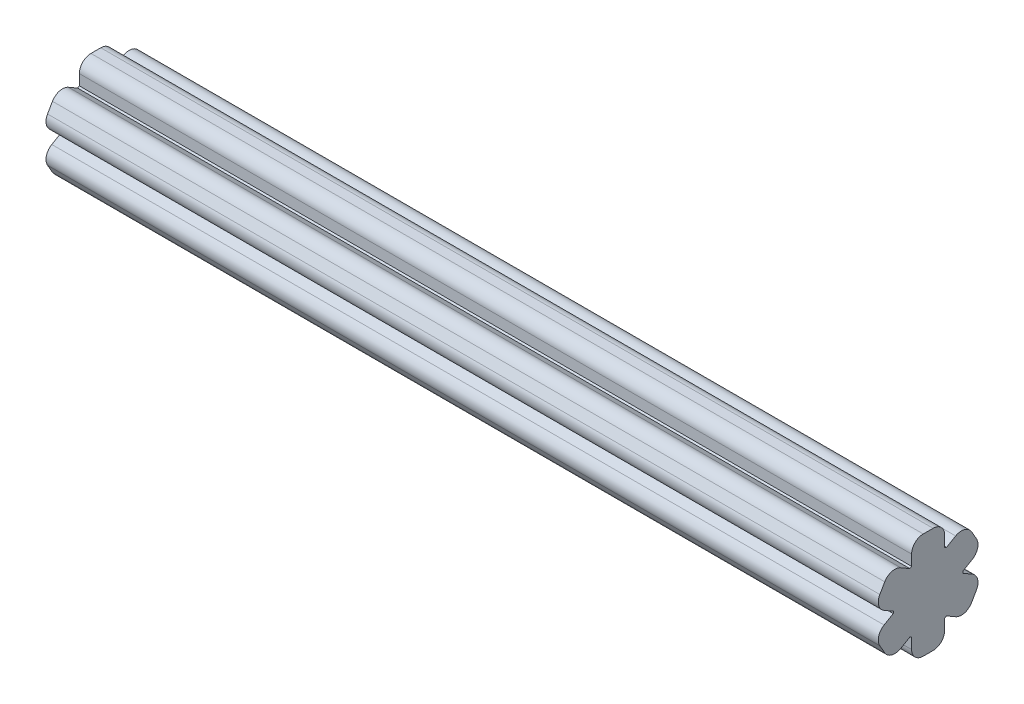
SolidWorks part; units mm, degrees
other "Markup1"
sketch "Sketch9" plane through (0, -25.79, -25.79) normal (-1, 0, 0) x (0, 1, 0)
ref_plane "Front Plane" through (0, 0, 0) normal (0, 0, 1) x (1, 0, 0)
ref_plane "Top Plane" through (0, 0, 0) normal (0, 1, 0) x (1, 0, 0)
ref_plane "Right Plane" through (0, 0, 0) normal (1, 0, 0) x (0, 0, -1)
sketch "Sketch2" plane through (0, 0, 0) normal (1, 0, 0) x (0, 0, -1)
  line L0 (9.5217, 3.0557) -> (16.4499, 7.0557)
  line L1 (-2.1146, 17.7739) -> (-2.1146, 9.7739)
  line L2 (-2.1146, 9.7739) -> (-2.1146, 17.7739)
  line L3 (2.1146, 17.7739) -> (-2.1146, 17.7739)
  line L4 (2.1146, 9.7739) -> (2.1146, 17.7739)
  line L5 (0, 17.7739) -> (0, 0) construction
  line L6 (16.4499, 7.0557) -> (14.3353, 10.7182)
  line L7 (14.3353, 10.7182) -> (7.4071, 6.7182)
  line L8 (7.4071, -6.7182) -> (14.3353, -10.7182)
  line L9 (14.3353, -10.7182) -> (16.4499, -7.0557)
  line L10 (16.4499, -7.0557) -> (9.5217, -3.0557)
  line L11 (-2.1146, -9.7739) -> (-2.1146, -17.7739)
  line L12 (-2.1146, -17.7739) -> (2.1146, -17.7739)
  line L13 (2.1146, -17.7739) -> (2.1146, -9.7739)
  line L14 (-9.5217, -3.0557) -> (-16.4499, -7.0557)
  line L15 (-16.4499, -7.0557) -> (-14.3353, -10.7182)
  line L16 (-14.3353, -10.7182) -> (-7.4071, -6.7182)
  line L17 (-7.4071, 6.7182) -> (-14.3353, 10.7182)
  line L18 (-14.3353, 10.7182) -> (-16.4499, 7.0557)
  line L19 (-16.4499, 7.0557) -> (-9.5217, 3.0557)
  circle A0 centre (0, 0) radius 25.79
  arc A1 (-2.1146, 9.7739) -> (-7.4071, 6.7182) centre (0, 0) ccw
  arc A2 (-9.5217, 3.0557) -> (-9.5217, -3.0557) centre (0, 0) ccw
  arc A3 (-7.4071, -6.7182) -> (-2.1146, -9.7739) centre (0, 0) ccw
  arc A4 (2.1146, -9.7739) -> (7.4071, -6.7182) centre (0, 0) ccw
  arc A5 (9.5217, -3.0557) -> (9.5217, 3.0557) centre (0, 0) ccw
  arc A6 (7.4071, 6.7182) -> (2.1146, 9.7739) centre (0, 0) ccw
  point P32 (0, 0)
  dimension "D1" = 6
  dimension "D2" = 51.58
  dimension "D4" = 4.2291
  dimension "10" = 10
  dimension "D3" = 8
extrude "Boss-Extrude2" add sketch "Sketch2" along normal blind 358 contours A0 | L17 L18 L19 A2 L14 L15 L16 A3 L11 L12 L13 A4 L8 L9 L10 A5 L0 L6 L7 A6 L4 L3 L1 A1
sketch "Sketch3" plane through (0, 0, 0) normal (-1, 0, 0) x (0, 0, 1)
  line L262 (-3.1146, -10.5499) -> (-3.1146, -18.7739)
  line L263 (-3.1146, -18.7739) -> (3.1146, -18.7739)
  line L264 (3.1146, -18.7739) -> (3.1146, -10.5499)
  line L265 (7.5792, -7.9722) -> (14.7014, -12.0842)
  line L266 (14.7014, -12.0842) -> (17.8159, -6.6896)
  line L267 (17.8159, -6.6896) -> (10.6937, -2.5776)
  line L268 (10.6937, 2.5776) -> (17.8159, 6.6896)
  line L269 (17.8159, 6.6896) -> (14.7014, 12.0842)
  line L270 (14.7014, 12.0842) -> (7.5792, 7.9722)
  line L271 (3.1146, 10.5499) -> (3.1146, 18.7739)
  line L272 (3.1146, 18.7739) -> (-3.1146, 18.7739)
  line L273 (-3.1146, 18.7739) -> (-3.1146, 10.5499)
  line L274 (-7.5792, 7.9722) -> (-14.7014, 12.0842)
  line L275 (-14.7014, 12.0842) -> (-17.8159, 6.6896)
  line L276 (-17.8159, 6.6896) -> (-10.6937, 2.5776)
  line L277 (-10.6937, -2.5776) -> (-17.8159, -6.6896)
  line L278 (-14.7014, -12.0842) -> (-7.5792, -7.9722)
  line L279 (-17.8159, -6.6896) -> (-14.7014, -12.0842)
  line L280 (-3.1146, -10.5499) -> (-3.1146, -17.7739)
  line L281 (-2.1146, -18.7739) -> (2.1146, -18.7739)
  line L282 (3.1146, -17.7739) -> (3.1146, -10.5499)
  line L283 (7.5792, -7.9722) -> (13.8353, -11.5842)
  line L284 (15.2014, -11.2182) -> (17.3159, -7.5557)
  line L285 (16.9499, -6.1896) -> (10.6937, -2.5776)
  line L286 (10.6937, 2.5776) -> (16.9499, 6.1896)
  line L287 (17.3159, 7.5557) -> (15.2014, 11.2182)
  line L288 (13.8353, 11.5842) -> (7.5792, 7.9722)
  line L289 (3.1146, 10.5499) -> (3.1146, 17.7739)
  line L290 (2.1146, 18.7739) -> (-2.1146, 18.7739)
  line L291 (-3.1146, 17.7739) -> (-3.1146, 10.5499)
  line L292 (-7.5792, 7.9722) -> (-13.8353, 11.5842)
  line L293 (-15.2014, 11.2182) -> (-17.3159, 7.5557)
  line L294 (-16.9499, 6.1896) -> (-10.6937, 2.5776)
  line L295 (-10.6937, -2.5776) -> (-16.9499, -6.1896)
  line L296 (-13.8353, -11.5842) -> (-7.5792, -7.9722)
  line L297 (-17.3159, -7.5557) -> (-15.2014, -11.2182)
  arc A69 (-3.1146, -17.7739) -> (-2.1146, -18.7739) centre (-2.1146, -17.7739) ccw
  arc A70 (2.1146, -18.7739) -> (3.1146, -17.7739) centre (2.1146, -17.7739) ccw
  arc A71 (13.8353, -11.5842) -> (15.2014, -11.2182) centre (14.3353, -10.7182) ccw
  arc A72 (17.3159, -7.5557) -> (16.9499, -6.1896) centre (16.4499, -7.0557) ccw
  arc A73 (16.9499, 6.1896) -> (17.3159, 7.5557) centre (16.4499, 7.0557) ccw
  arc A74 (15.2014, 11.2182) -> (13.8353, 11.5842) centre (14.3353, 10.7182) ccw
  arc A75 (-7.5792, -7.9722) -> (-3.1146, -10.5499) centre (0, 0) ccw
  arc A76 (3.1146, -10.5499) -> (7.5792, -7.9722) centre (0, 0) ccw
  arc A77 (10.6937, -2.5776) -> (10.6937, 2.5776) centre (0, 0) ccw
  arc A78 (7.5792, 7.9722) -> (3.1146, 10.5499) centre (0, 0) ccw
  arc A79 (-3.1146, 10.5499) -> (-7.5792, 7.9722) centre (0, 0) ccw
  arc A80 (-10.6937, 2.5776) -> (-10.6937, -2.5776) centre (0, 0) ccw
  arc A81 (-7.5792, -7.9722) -> (-3.1146, -10.5499) centre (0, 0) ccw
  arc A82 (3.1146, -10.5499) -> (7.5792, -7.9722) centre (0, 0) ccw
  arc A83 (10.6937, -2.5776) -> (10.6937, 2.5776) centre (0, 0) ccw
  arc A84 (7.5792, 7.9722) -> (3.1146, 10.5499) centre (0, 0) ccw
  arc A85 (-3.1146, 10.5499) -> (-7.5792, 7.9722) centre (0, 0) ccw
  arc A86 (-10.6937, 2.5776) -> (-10.6937, -2.5776) centre (0, 0) ccw
  arc A87 (3.1146, 17.7739) -> (2.1146, 18.7739) centre (2.1146, 17.7739) ccw
  arc A88 (-2.1146, 18.7739) -> (-3.1146, 17.7739) centre (-2.1146, 17.7739) ccw
  arc A89 (-15.2014, 11.2182) -> (-13.8353, 11.5842) centre (-14.3353, 10.7182) cw
  arc A90 (-17.3159, 7.5557) -> (-16.9499, 6.1896) centre (-16.4499, 7.0557) ccw
  arc A91 (-16.9499, -6.1896) -> (-17.3159, -7.5557) centre (-16.4499, -7.0557) ccw
  arc A92 (-15.2014, -11.2182) -> (-13.8353, -11.5842) centre (-14.3353, -10.7182) ccw
  point P41 (-9.7909, -2.6337)
  point P43 (0, 0)
  point P46 (-9.7344, -2.2892)
  point P47 (0, 0)
  dimension "D2" = 1
  dimension "D1" = 1
sketch "Sketch5" plane through (0, 0, 0) normal (-1, 0, 0) x (0, 0, 1)
  line L72 (-4.1146, -11.2725) -> (-4.1146, -17.7739)
  line L73 (-2.1146, -19.7739) -> (2.1146, -19.7739)
  line L74 (4.1146, -17.7739) -> (4.1146, -11.2725)
  line L75 (7.705, -9.1996) -> (13.3353, -12.4503)
  line L76 (16.0674, -11.7182) -> (18.182, -8.0557)
  line L77 (17.4499, -5.3236) -> (11.8196, -2.073)
  line L78 (11.8196, 2.073) -> (17.4499, 5.3236)
  line L79 (18.182, 8.0557) -> (16.0674, 11.7182)
  line L80 (13.3353, 12.4503) -> (7.705, 9.1996)
  line L81 (4.1146, 11.2725) -> (4.1146, 17.7739)
  line L82 (2.1146, 19.7739) -> (-2.1146, 19.7739)
  line L83 (-4.1146, 17.7739) -> (-4.1146, 11.2725)
  line L84 (-7.705, 9.1996) -> (-13.3353, 12.4503)
  line L85 (-16.0674, 11.7182) -> (-18.182, 8.0557)
  line L86 (-17.4499, 5.3236) -> (-11.8196, 2.073)
  line L87 (-11.8196, -2.073) -> (-17.4499, -5.3236)
  line L88 (-18.182, -8.0557) -> (-16.0674, -11.7182)
  line L89 (-13.3353, -12.4503) -> (-7.705, -9.1996)
  line L90 (-4.1146, -11.2725) -> (-4.1146, -17.7739)
  line L91 (-2.1146, -19.7739) -> (2.1146, -19.7739)
  line L92 (4.1146, -17.7739) -> (4.1146, -11.2725)
  line L93 (7.705, -9.1996) -> (13.3353, -12.4503)
  line L94 (16.0674, -11.7182) -> (18.182, -8.0557)
  line L95 (17.4499, -5.3236) -> (11.8196, -2.073)
  line L96 (11.8196, 2.073) -> (17.4499, 5.3236)
  line L97 (18.182, 8.0557) -> (16.0674, 11.7182)
  line L98 (13.3353, 12.4503) -> (7.705, 9.1996)
  line L99 (4.1146, 11.2725) -> (4.1146, 17.7739)
  line L100 (2.1146, 19.7739) -> (-2.1146, 19.7739)
  line L101 (-4.1146, 17.7739) -> (-4.1146, 11.2725)
  line L102 (-7.705, 9.1996) -> (-13.3353, 12.4503)
  line L103 (-16.0674, 11.7182) -> (-18.182, 8.0557)
  line L104 (-17.4499, 5.3236) -> (-11.8196, 2.073)
  line L105 (-11.8196, -2.073) -> (-17.4499, -5.3236)
  line L106 (-18.182, -8.0557) -> (-16.0674, -11.7182)
  line L107 (-13.3353, -12.4503) -> (-7.705, -9.1996)
  arc A72 (-4.1146, -17.7739) -> (-2.1146, -19.7739) centre (-2.1146, -17.7739) ccw
  arc A73 (2.1146, -19.7739) -> (4.1146, -17.7739) centre (2.1146, -17.7739) ccw
  arc A74 (4.1146, -11.2725) -> (7.705, -9.1996) centre (0, 0) ccw
  arc A75 (13.3353, -12.4503) -> (16.0674, -11.7182) centre (14.3353, -10.7182) ccw
  arc A76 (18.182, -8.0557) -> (17.4499, -5.3236) centre (16.4499, -7.0557) ccw
  arc A77 (11.8196, -2.073) -> (11.8196, 2.073) centre (0, 0) ccw
  arc A78 (17.4499, 5.3236) -> (18.182, 8.0557) centre (16.4499, 7.0557) ccw
  arc A79 (16.0674, 11.7182) -> (13.3353, 12.4503) centre (14.3353, 10.7182) ccw
  arc A80 (7.705, 9.1996) -> (4.1146, 11.2725) centre (0, 0) ccw
  arc A81 (4.1146, 17.7739) -> (2.1146, 19.7739) centre (2.1146, 17.7739) ccw
  arc A82 (-2.1146, 19.7739) -> (-4.1146, 17.7739) centre (-2.1146, 17.7739) ccw
  arc A83 (-4.1146, 11.2725) -> (-7.705, 9.1996) centre (0, 0) ccw
  arc A84 (-13.3353, 12.4503) -> (-16.0674, 11.7182) centre (-14.3353, 10.7182) ccw
  arc A85 (-18.182, 8.0557) -> (-17.4499, 5.3236) centre (-16.4499, 7.0557) ccw
  arc A86 (-11.8196, 2.073) -> (-11.8196, -2.073) centre (0, 0) ccw
  arc A87 (-17.4499, -5.3236) -> (-18.182, -8.0557) centre (-16.4499, -7.0557) ccw
  arc A88 (-16.0674, -11.7182) -> (-13.3353, -12.4503) centre (-14.3353, -10.7182) ccw
  arc A89 (-7.705, -9.1996) -> (-4.1146, -11.2725) centre (0, 0) ccw
  arc A90 (-4.1146, -17.7739) -> (-2.1146, -19.7739) centre (-2.1146, -17.7739) ccw
  arc A91 (2.1146, -19.7739) -> (4.1146, -17.7739) centre (2.1146, -17.7739) ccw
  arc A92 (4.1146, -11.2725) -> (7.705, -9.1996) centre (0, 0) ccw
  arc A93 (13.3353, -12.4503) -> (16.0674, -11.7182) centre (14.3353, -10.7182) ccw
  arc A94 (18.182, -8.0557) -> (17.4499, -5.3236) centre (16.4499, -7.0557) ccw
  arc A95 (11.8196, -2.073) -> (11.8196, 2.073) centre (0, 0) ccw
  arc A96 (17.4499, 5.3236) -> (18.182, 8.0557) centre (16.4499, 7.0557) ccw
  arc A97 (16.0674, 11.7182) -> (13.3353, 12.4503) centre (14.3353, 10.7182) ccw
  arc A98 (7.705, 9.1996) -> (4.1146, 11.2725) centre (0, 0) ccw
  arc A99 (4.1146, 17.7739) -> (2.1146, 19.7739) centre (2.1146, 17.7739) ccw
  arc A100 (-2.1146, 19.7739) -> (-4.1146, 17.7739) centre (-2.1146, 17.7739) ccw
  arc A101 (-4.1146, 11.2725) -> (-7.705, 9.1996) centre (0, 0) ccw
  arc A102 (-13.3353, 12.4503) -> (-16.0674, 11.7182) centre (-14.3353, 10.7182) ccw
  arc A103 (-18.182, 8.0557) -> (-17.4499, 5.3236) centre (-16.4499, 7.0557) ccw
  arc A104 (-11.8196, 2.073) -> (-11.8196, -2.073) centre (0, 0) ccw
  arc A105 (-17.4499, -5.3236) -> (-18.182, -8.0557) centre (-16.4499, -7.0557) ccw
  arc A106 (-16.0674, -11.7182) -> (-13.3353, -12.4503) centre (-14.3353, -10.7182) ccw
  arc A107 (-7.705, -9.1996) -> (-4.1146, -11.2725) centre (0, 0) ccw
  dimension "D1" = 1
sketch "Sketch6" plane through (0, 0, 0) normal (-1, 0, 0) x (0, 0, 1)
  line L37 (-5.1146, -11.9516) -> (-5.1146, -17.7739)
  line L38 (-2.1146, -20.7739) -> (2.1146, -20.7739)
  line L39 (5.1146, -17.7739) -> (5.1146, -11.9516)
  line L40 (7.7931, -10.4052) -> (12.8353, -13.3163)
  line L41 (16.9334, -12.2182) -> (19.048, -8.5557)
  line L42 (17.9499, -4.4576) -> (12.9077, -1.5465)
  line L43 (12.9077, 1.5465) -> (17.9499, 4.4576)
  line L44 (19.048, 8.5557) -> (16.9334, 12.2182)
  line L45 (12.8353, 13.3163) -> (7.7931, 10.4052)
  line L46 (5.1146, 11.9516) -> (5.1146, 17.7739)
  line L47 (2.1146, 20.7739) -> (-2.1146, 20.7739)
  line L48 (-5.1146, 17.7739) -> (-5.1146, 11.9516)
  line L49 (-7.7931, 10.4052) -> (-12.8353, 13.3163)
  line L50 (-16.9334, 12.2182) -> (-19.048, 8.5557)
  line L51 (-17.9499, 4.4576) -> (-12.9077, 1.5465)
  line L52 (-12.9077, -1.5465) -> (-17.9499, -4.4576)
  line L53 (-19.048, -8.5557) -> (-16.9334, -12.2182)
  line L54 (-12.8353, -13.3163) -> (-7.7931, -10.4052)
  line L55 (-5.1146, -11.9516) -> (-5.1146, -17.7739)
  line L56 (-2.1146, -20.7739) -> (2.1146, -20.7739)
  line L57 (5.1146, -17.7739) -> (5.1146, -11.9516)
  line L58 (7.7931, -10.4052) -> (12.8353, -13.3163)
  line L59 (16.9334, -12.2182) -> (19.048, -8.5557)
  line L60 (17.9499, -4.4576) -> (12.9077, -1.5465)
  line L61 (12.9077, 1.5465) -> (17.9499, 4.4576)
  line L62 (19.048, 8.5557) -> (16.9334, 12.2182)
  line L63 (12.8353, 13.3163) -> (7.7931, 10.4052)
  line L64 (5.1146, 11.9516) -> (5.1146, 17.7739)
  line L65 (2.1146, 20.7739) -> (-2.1146, 20.7739)
  line L66 (-5.1146, 17.7739) -> (-5.1146, 11.9516)
  line L67 (-7.7931, 10.4052) -> (-12.8353, 13.3163)
  line L68 (-16.9334, 12.2182) -> (-19.048, 8.5557)
  line L69 (-17.9499, 4.4576) -> (-12.9077, 1.5465)
  line L70 (-12.9077, -1.5465) -> (-17.9499, -4.4576)
  line L71 (-19.048, -8.5557) -> (-16.9334, -12.2182)
  line L72 (-12.8353, -13.3163) -> (-7.7931, -10.4052)
  arc A36 (-5.1146, -17.7739) -> (-2.1146, -20.7739) centre (-2.1146, -17.7739) ccw
  arc A37 (2.1146, -20.7739) -> (5.1146, -17.7739) centre (2.1146, -17.7739) ccw
  arc A38 (5.1146, -11.9516) -> (7.7931, -10.4052) centre (0, 0) ccw
  arc A39 (12.8353, -13.3163) -> (16.9334, -12.2182) centre (14.3353, -10.7182) ccw
  arc A40 (19.048, -8.5557) -> (17.9499, -4.4576) centre (16.4499, -7.0557) ccw
  arc A41 (12.9077, -1.5465) -> (12.9077, 1.5465) centre (0, 0) ccw
  arc A42 (17.9499, 4.4576) -> (19.048, 8.5557) centre (16.4499, 7.0557) ccw
  arc A43 (16.9334, 12.2182) -> (12.8353, 13.3163) centre (14.3353, 10.7182) ccw
  arc A44 (7.7931, 10.4052) -> (5.1146, 11.9516) centre (0, 0) ccw
  arc A45 (5.1146, 17.7739) -> (2.1146, 20.7739) centre (2.1146, 17.7739) ccw
  arc A46 (-2.1146, 20.7739) -> (-5.1146, 17.7739) centre (-2.1146, 17.7739) ccw
  arc A47 (-5.1146, 11.9516) -> (-7.7931, 10.4052) centre (0, 0) ccw
  arc A48 (-12.8353, 13.3163) -> (-16.9334, 12.2182) centre (-14.3353, 10.7182) ccw
  arc A49 (-19.048, 8.5557) -> (-17.9499, 4.4576) centre (-16.4499, 7.0557) ccw
  arc A50 (-12.9077, 1.5465) -> (-12.9077, -1.5465) centre (0, 0) ccw
  arc A51 (-17.9499, -4.4576) -> (-19.048, -8.5557) centre (-16.4499, -7.0557) ccw
  arc A52 (-16.9334, -12.2182) -> (-12.8353, -13.3163) centre (-14.3353, -10.7182) ccw
  arc A53 (-7.7931, -10.4052) -> (-5.1146, -11.9516) centre (0, 0) ccw
  arc A54 (-5.1146, -17.7739) -> (-2.1146, -20.7739) centre (-2.1146, -17.7739) ccw
  arc A55 (2.1146, -20.7739) -> (5.1146, -17.7739) centre (2.1146, -17.7739) ccw
  arc A56 (5.1146, -11.9516) -> (7.7931, -10.4052) centre (0, 0) ccw
  arc A57 (12.8353, -13.3163) -> (16.9334, -12.2182) centre (14.3353, -10.7182) ccw
  arc A58 (19.048, -8.5557) -> (17.9499, -4.4576) centre (16.4499, -7.0557) ccw
  arc A59 (12.9077, -1.5465) -> (12.9077, 1.5465) centre (0, 0) ccw
  arc A60 (17.9499, 4.4576) -> (19.048, 8.5557) centre (16.4499, 7.0557) ccw
  arc A61 (16.9334, 12.2182) -> (12.8353, 13.3163) centre (14.3353, 10.7182) ccw
  arc A62 (7.7931, 10.4052) -> (5.1146, 11.9516) centre (0, 0) ccw
  arc A63 (5.1146, 17.7739) -> (2.1146, 20.7739) centre (2.1146, 17.7739) ccw
  arc A64 (-2.1146, 20.7739) -> (-5.1146, 17.7739) centre (-2.1146, 17.7739) ccw
  arc A65 (-5.1146, 11.9516) -> (-7.7931, 10.4052) centre (0, 0) ccw
  arc A66 (-12.8353, 13.3163) -> (-16.9334, 12.2182) centre (-14.3353, 10.7182) ccw
  arc A67 (-19.048, 8.5557) -> (-17.9499, 4.4576) centre (-16.4499, 7.0557) ccw
  arc A68 (-12.9077, 1.5465) -> (-12.9077, -1.5465) centre (0, 0) ccw
  arc A69 (-17.9499, -4.4576) -> (-19.048, -8.5557) centre (-16.4499, -7.0557) ccw
  arc A70 (-16.9334, -12.2182) -> (-12.8353, -13.3163) centre (-14.3353, -10.7182) ccw
  arc A71 (-7.7931, -10.4052) -> (-5.1146, -11.9516) centre (0, 0) ccw
  dimension "D1" = 1
sketch "Sketch7" plane through (0, 0, 0) normal (-1, 0, 0) x (0, 0, 1)
  line L36 (-6.1146, -12.5941) -> (-6.1146, -17.7739)
  line L37 (-2.1146, -21.7739) -> (2.1146, -21.7739)
  line L38 (6.1146, -17.7739) -> (6.1146, -12.5941)
  line L39 (7.8496, -11.5924) -> (12.3353, -14.1823)
  line L40 (17.7994, -12.7182) -> (19.914, -9.0557)
  line L41 (18.4499, -3.5916) -> (13.9641, -1.0017)
  line L42 (13.9641, 1.0017) -> (18.4499, 3.5916)
  line L43 (19.914, 9.0557) -> (17.7994, 12.7182)
  line L44 (12.3353, 14.1823) -> (7.8496, 11.5924)
  line L45 (6.1146, 12.5941) -> (6.1146, 17.7739)
  line L46 (2.1146, 21.7739) -> (-2.1146, 21.7739)
  line L47 (-6.1146, 17.7739) -> (-6.1146, 12.5941)
  line L48 (-7.8496, 11.5924) -> (-12.3353, 14.1823)
  line L49 (-17.7994, 12.7182) -> (-19.914, 9.0557)
  line L50 (-18.4499, 3.5916) -> (-13.9641, 1.0017)
  line L51 (-13.9641, -1.0017) -> (-18.4499, -3.5916)
  line L52 (-19.914, -9.0557) -> (-17.7994, -12.7182)
  line L53 (-12.3353, -14.1823) -> (-7.8496, -11.5924)
  line L54 (-6.1146, -12.5941) -> (-6.1146, -17.7739)
  line L55 (-2.1146, -21.7739) -> (2.1146, -21.7739)
  line L56 (6.1146, -17.7739) -> (6.1146, -12.5941)
  line L57 (7.8496, -11.5924) -> (12.3353, -14.1823)
  line L58 (17.7994, -12.7182) -> (19.914, -9.0557)
  line L59 (18.4499, -3.5916) -> (13.9641, -1.0017)
  line L60 (13.9641, 1.0017) -> (18.4499, 3.5916)
  line L61 (19.914, 9.0557) -> (17.7994, 12.7182)
  line L62 (12.3353, 14.1823) -> (7.8496, 11.5924)
  line L63 (6.1146, 12.5941) -> (6.1146, 17.7739)
  line L64 (2.1146, 21.7739) -> (-2.1146, 21.7739)
  line L65 (-6.1146, 17.7739) -> (-6.1146, 12.5941)
  line L66 (-7.8496, 11.5924) -> (-12.3353, 14.1823)
  line L67 (-17.7994, 12.7182) -> (-19.914, 9.0557)
  line L68 (-18.4499, 3.5916) -> (-13.9641, 1.0017)
  line L69 (-13.9641, -1.0017) -> (-18.4499, -3.5916)
  line L70 (-19.914, -9.0557) -> (-17.7994, -12.7182)
  line L71 (-12.3353, -14.1823) -> (-7.8496, -11.5924)
  arc A37 (-6.1146, -17.7739) -> (-2.1146, -21.7739) centre (-2.1146, -17.7739) ccw
  arc A38 (2.1146, -21.7739) -> (6.1146, -17.7739) centre (2.1146, -17.7739) ccw
  arc A39 (6.1146, -12.5941) -> (7.8496, -11.5924) centre (0, 0) ccw
  arc A40 (12.3353, -14.1823) -> (17.7994, -12.7182) centre (14.3353, -10.7182) ccw
  arc A41 (19.914, -9.0557) -> (18.4499, -3.5916) centre (16.4499, -7.0557) ccw
  arc A42 (13.9641, -1.0017) -> (13.9641, 1.0017) centre (0, 0) ccw
  arc A43 (18.4499, 3.5916) -> (19.914, 9.0557) centre (16.4499, 7.0557) ccw
  arc A44 (17.7994, 12.7182) -> (12.3353, 14.1823) centre (14.3353, 10.7182) ccw
  arc A45 (7.8496, 11.5924) -> (6.1146, 12.5941) centre (0, 0) ccw
  arc A46 (6.1146, 17.7739) -> (2.1146, 21.7739) centre (2.1146, 17.7739) ccw
  arc A47 (-2.1146, 21.7739) -> (-6.1146, 17.7739) centre (-2.1146, 17.7739) ccw
  arc A48 (-6.1146, 12.5941) -> (-7.8496, 11.5924) centre (0, 0) ccw
  arc A49 (-12.3353, 14.1823) -> (-17.7994, 12.7182) centre (-14.3353, 10.7182) ccw
  arc A50 (-19.914, 9.0557) -> (-18.4499, 3.5916) centre (-16.4499, 7.0557) ccw
  arc A51 (-13.9641, 1.0017) -> (-13.9641, -1.0017) centre (0, 0) ccw
  arc A52 (-18.4499, -3.5916) -> (-19.914, -9.0557) centre (-16.4499, -7.0557) ccw
  arc A53 (-17.7994, -12.7182) -> (-12.3353, -14.1823) centre (-14.3353, -10.7182) ccw
  arc A54 (-7.8496, -11.5924) -> (-6.1146, -12.5941) centre (0, 0) ccw
  arc A55 (-6.1146, -17.7739) -> (-2.1146, -21.7739) centre (-2.1146, -17.7739) ccw
  arc A56 (2.1146, -21.7739) -> (6.1146, -17.7739) centre (2.1146, -17.7739) ccw
  arc A57 (6.1146, -12.5941) -> (7.8496, -11.5924) centre (0, 0) ccw
  arc A58 (12.3353, -14.1823) -> (17.7994, -12.7182) centre (14.3353, -10.7182) ccw
  arc A59 (19.914, -9.0557) -> (18.4499, -3.5916) centre (16.4499, -7.0557) ccw
  arc A60 (13.9641, -1.0017) -> (13.9641, 1.0017) centre (0, 0) ccw
  arc A61 (18.4499, 3.5916) -> (19.914, 9.0557) centre (16.4499, 7.0557) ccw
  arc A62 (17.7994, 12.7182) -> (12.3353, 14.1823) centre (14.3353, 10.7182) ccw
  arc A63 (7.8496, 11.5924) -> (6.1146, 12.5941) centre (0, 0) ccw
  arc A64 (6.1146, 17.7739) -> (2.1146, 21.7739) centre (2.1146, 17.7739) ccw
  arc A65 (-2.1146, 21.7739) -> (-6.1146, 17.7739) centre (-2.1146, 17.7739) ccw
  arc A66 (-6.1146, 12.5941) -> (-7.8496, 11.5924) centre (0, 0) ccw
  arc A67 (-12.3353, 14.1823) -> (-17.7994, 12.7182) centre (-14.3353, 10.7182) ccw
  arc A68 (-19.914, 9.0557) -> (-18.4499, 3.5916) centre (-16.4499, 7.0557) ccw
  arc A69 (-13.9641, 1.0017) -> (-13.9641, -1.0017) centre (0, 0) ccw
  arc A70 (-18.4499, -3.5916) -> (-19.914, -9.0557) centre (-16.4499, -7.0557) ccw
  arc A71 (-17.7994, -12.7182) -> (-12.3353, -14.1823) centre (-14.3353, -10.7182) ccw
  arc A72 (-7.8496, -11.5924) -> (-6.1146, -12.5941) centre (0, 0) ccw
  dimension "D1" = 1
sketch "Sketch10" plane through (0, 0, 0) normal (-1, 0, 0) x (0, 0, 1)
  line L36 (-7.1146, -13.2054) -> (-7.1146, -17.7739)
  line L37 (-2.1146, -22.7739) -> (2.1146, -22.7739)
  line L38 (7.1146, -17.7739) -> (7.1146, -13.2054)
  line L39 (7.8789, -12.7641) -> (11.8353, -15.0483)
  line L40 (18.6655, -13.2182) -> (20.78, -9.5557)
  line L41 (18.9499, -2.7255) -> (14.9935, -0.4413)
  line L42 (14.9935, 0.4413) -> (18.9499, 2.7255)
  line L43 (20.78, 9.5557) -> (18.6655, 13.2182)
  line L44 (11.8353, 15.0483) -> (7.8789, 12.7641)
  line L45 (7.1146, 13.2054) -> (7.1146, 17.7739)
  line L46 (2.1146, 22.7739) -> (-2.1146, 22.7739)
  line L47 (-7.1146, 17.7739) -> (-7.1146, 13.2054)
  line L48 (-7.8789, 12.7641) -> (-11.8353, 15.0483)
  line L49 (-18.6655, 13.2182) -> (-20.78, 9.5557)
  line L50 (-18.9499, 2.7255) -> (-14.9935, 0.4413)
  line L51 (-14.9935, -0.4413) -> (-18.9499, -2.7255)
  line L52 (-20.78, -9.5557) -> (-18.6655, -13.2182)
  line L53 (-11.8353, -15.0483) -> (-7.8789, -12.7641)
  line L54 (-7.1146, -13.2054) -> (-7.1146, -17.7739)
  line L55 (-2.1146, -22.7739) -> (2.1146, -22.7739)
  line L56 (7.1146, -17.7739) -> (7.1146, -13.2054)
  line L57 (7.8789, -12.7641) -> (11.8353, -15.0483)
  line L58 (18.6655, -13.2182) -> (20.78, -9.5557)
  line L59 (18.9499, -2.7255) -> (14.9935, -0.4413)
  line L60 (14.9935, 0.4413) -> (18.9499, 2.7255)
  line L61 (20.78, 9.5557) -> (18.6655, 13.2182)
  line L62 (11.8353, 15.0483) -> (7.8789, 12.7641)
  line L63 (7.1146, 13.2054) -> (7.1146, 17.7739)
  line L64 (2.1146, 22.7739) -> (-2.1146, 22.7739)
  line L65 (-7.1146, 17.7739) -> (-7.1146, 13.2054)
  line L66 (-7.8789, 12.7641) -> (-11.8353, 15.0483)
  line L67 (-18.6655, 13.2182) -> (-20.78, 9.5557)
  line L68 (-18.9499, 2.7255) -> (-14.9935, 0.4413)
  line L69 (-14.9935, -0.4413) -> (-18.9499, -2.7255)
  line L70 (-20.78, -9.5557) -> (-18.6655, -13.2182)
  line L71 (-11.8353, -15.0483) -> (-7.8789, -12.7641)
  arc A36 (-7.1146, -17.7739) -> (-2.1146, -22.7739) centre (-2.1146, -17.7739) ccw
  arc A37 (2.1146, -22.7739) -> (7.1146, -17.7739) centre (2.1146, -17.7739) ccw
  arc A38 (7.1146, -13.2054) -> (7.8789, -12.7641) centre (0, 0) ccw
  arc A39 (11.8353, -15.0483) -> (18.6655, -13.2182) centre (14.3353, -10.7182) ccw
  arc A40 (20.78, -9.5557) -> (18.9499, -2.7255) centre (16.4499, -7.0557) ccw
  arc A41 (14.9935, -0.4413) -> (14.9935, 0.4413) centre (0, 0) ccw
  arc A42 (18.9499, 2.7255) -> (20.78, 9.5557) centre (16.4499, 7.0557) ccw
  arc A43 (18.6655, 13.2182) -> (11.8353, 15.0483) centre (14.3353, 10.7182) ccw
  arc A44 (7.8789, 12.7641) -> (7.1146, 13.2054) centre (0, 0) ccw
  arc A45 (7.1146, 17.7739) -> (2.1146, 22.7739) centre (2.1146, 17.7739) ccw
  arc A46 (-2.1146, 22.7739) -> (-7.1146, 17.7739) centre (-2.1146, 17.7739) ccw
  arc A47 (-7.1146, 13.2054) -> (-7.8789, 12.7641) centre (0, 0) ccw
  arc A48 (-11.8353, 15.0483) -> (-18.6655, 13.2182) centre (-14.3353, 10.7182) ccw
  arc A49 (-20.78, 9.5557) -> (-18.9499, 2.7255) centre (-16.4499, 7.0557) ccw
  arc A50 (-14.9935, 0.4413) -> (-14.9935, -0.4413) centre (0, 0) ccw
  arc A51 (-18.9499, -2.7255) -> (-20.78, -9.5557) centre (-16.4499, -7.0557) ccw
  arc A52 (-18.6655, -13.2182) -> (-11.8353, -15.0483) centre (-14.3353, -10.7182) ccw
  arc A53 (-7.8789, -12.7641) -> (-7.1146, -13.2054) centre (0, 0) ccw
  arc A54 (-7.1146, -17.7739) -> (-2.1146, -22.7739) centre (-2.1146, -17.7739) ccw
  arc A55 (2.1146, -22.7739) -> (7.1146, -17.7739) centre (2.1146, -17.7739) ccw
  arc A56 (7.1146, -13.2054) -> (7.8789, -12.7641) centre (0, 0) ccw
  arc A57 (11.8353, -15.0483) -> (18.6655, -13.2182) centre (14.3353, -10.7182) ccw
  arc A58 (20.78, -9.5557) -> (18.9499, -2.7255) centre (16.4499, -7.0557) ccw
  arc A59 (14.9935, -0.4413) -> (14.9935, 0.4413) centre (0, 0) ccw
  arc A60 (18.9499, 2.7255) -> (20.78, 9.5557) centre (16.4499, 7.0557) ccw
  arc A61 (18.6655, 13.2182) -> (11.8353, 15.0483) centre (14.3353, 10.7182) ccw
  arc A62 (7.8789, 12.7641) -> (7.1146, 13.2054) centre (0, 0) ccw
  arc A63 (7.1146, 17.7739) -> (2.1146, 22.7739) centre (2.1146, 17.7739) ccw
  arc A64 (-2.1146, 22.7739) -> (-7.1146, 17.7739) centre (-2.1146, 17.7739) ccw
  arc A65 (-7.1146, 13.2054) -> (-7.8789, 12.7641) centre (0, 0) ccw
  arc A66 (-11.8353, 15.0483) -> (-18.6655, 13.2182) centre (-14.3353, 10.7182) ccw
  arc A67 (-20.78, 9.5557) -> (-18.9499, 2.7255) centre (-16.4499, 7.0557) ccw
  arc A68 (-14.9935, 0.4413) -> (-14.9935, -0.4413) centre (0, 0) ccw
  arc A69 (-18.9499, -2.7255) -> (-20.78, -9.5557) centre (-16.4499, -7.0557) ccw
  arc A70 (-18.6655, -13.2182) -> (-11.8353, -15.0483) centre (-14.3353, -10.7182) ccw
  arc A71 (-7.8789, -12.7641) -> (-7.1146, -13.2054) centre (0, 0) ccw
  dimension "D1" = 1
sketch "Sketch11" plane through (0, 0, 0) normal (-1, 0, 0) x (0, 0, 1)
  line L36 (-8.1146, -14.0548) -> (-8.1146, -17.7739)
  line L37 (-2.1146, -23.7739) -> (2.1146, -23.7739)
  line L38 (8.1146, -17.7739) -> (8.1146, -14.0548)
  line L39 (8.1146, -14.0548) -> (11.3353, -15.9144)
  line L40 (19.5315, -13.7182) -> (21.6461, -10.0557)
  line L41 (19.4499, -1.8595) -> (16.2291, 0)
  line L42 (16.2291, 0) -> (19.4499, 1.8595)
  line L43 (21.6461, 10.0557) -> (19.5315, 13.7182)
  line L44 (11.3353, 15.9144) -> (8.1146, 14.0548)
  line L45 (8.1146, 14.0548) -> (8.1146, 17.7739)
  line L46 (2.1146, 23.7739) -> (-2.1146, 23.7739)
  line L47 (-8.1146, 17.7739) -> (-8.1146, 14.0548)
  line L48 (-8.1146, 14.0548) -> (-11.3353, 15.9144)
  line L49 (-19.5315, 13.7182) -> (-21.6461, 10.0557)
  line L50 (-19.4499, 1.8595) -> (-16.2291, 0)
  line L51 (-16.2291, 0) -> (-19.4499, -1.8595)
  line L52 (-21.6461, -10.0557) -> (-19.5315, -13.7182)
  line L53 (-11.3353, -15.9144) -> (-8.1146, -14.0548)
  line L54 (-8.1146, -14.0548) -> (-8.1146, -17.7739)
  line L55 (-2.1146, -23.7739) -> (2.1146, -23.7739)
  line L56 (8.1146, -17.7739) -> (8.1146, -14.0548)
  line L57 (8.1146, -14.0548) -> (11.3353, -15.9144)
  line L58 (19.5315, -13.7182) -> (21.6461, -10.0557)
  line L59 (19.4499, -1.8595) -> (16.2291, 0)
  line L60 (16.2291, 0) -> (19.4499, 1.8595)
  line L61 (21.6461, 10.0557) -> (19.5315, 13.7182)
  line L62 (11.3353, 15.9144) -> (8.1146, 14.0548)
  line L63 (8.1146, 14.0548) -> (8.1146, 17.7739)
  line L64 (2.1146, 23.7739) -> (-2.1146, 23.7739)
  line L65 (-8.1146, 17.7739) -> (-8.1146, 14.0548)
  line L66 (-8.1146, 14.0548) -> (-11.3353, 15.9144)
  line L67 (-19.5315, 13.7182) -> (-21.6461, 10.0557)
  line L68 (-19.4499, 1.8595) -> (-16.2291, 0)
  line L69 (-16.2291, 0) -> (-19.4499, -1.8595)
  line L70 (-21.6461, -10.0557) -> (-19.5315, -13.7182)
  line L71 (-11.3353, -15.9144) -> (-8.1146, -14.0548)
  arc A36 (-8.1146, -17.7739) -> (-2.1146, -23.7739) centre (-2.1146, -17.7739) ccw
  arc A37 (2.1146, -23.7739) -> (8.1146, -17.7739) centre (2.1146, -17.7739) ccw
  arc A38 (11.3353, -15.9144) -> (19.5315, -13.7182) centre (14.3353, -10.7182) ccw
  arc A39 (21.6461, -10.0557) -> (19.4499, -1.8595) centre (16.4499, -7.0557) ccw
  arc A40 (19.4499, 1.8595) -> (21.6461, 10.0557) centre (16.4499, 7.0557) ccw
  arc A41 (19.5315, 13.7182) -> (11.3353, 15.9144) centre (14.3353, 10.7182) ccw
  arc A42 (8.1146, 17.7739) -> (2.1146, 23.7739) centre (2.1146, 17.7739) ccw
  arc A43 (-2.1146, 23.7739) -> (-8.1146, 17.7739) centre (-2.1146, 17.7739) ccw
  arc A44 (-11.3353, 15.9144) -> (-19.5315, 13.7182) centre (-14.3353, 10.7182) ccw
  arc A45 (-21.6461, 10.0557) -> (-19.4499, 1.8595) centre (-16.4499, 7.0557) ccw
  arc A46 (-19.4499, -1.8595) -> (-21.6461, -10.0557) centre (-16.4499, -7.0557) ccw
  arc A47 (-19.5315, -13.7182) -> (-11.3353, -15.9144) centre (-14.3353, -10.7182) ccw
  arc A48 (-8.1146, -17.7739) -> (-2.1146, -23.7739) centre (-2.1146, -17.7739) ccw
  arc A49 (2.1146, -23.7739) -> (8.1146, -17.7739) centre (2.1146, -17.7739) ccw
  arc A50 (11.3353, -15.9144) -> (19.5315, -13.7182) centre (14.3353, -10.7182) ccw
  arc A51 (21.6461, -10.0557) -> (19.4499, -1.8595) centre (16.4499, -7.0557) ccw
  arc A52 (19.4499, 1.8595) -> (21.6461, 10.0557) centre (16.4499, 7.0557) ccw
  arc A53 (19.5315, 13.7182) -> (11.3353, 15.9144) centre (14.3353, 10.7182) ccw
  arc A54 (8.1146, 17.7739) -> (2.1146, 23.7739) centre (2.1146, 17.7739) ccw
  arc A55 (-2.1146, 23.7739) -> (-8.1146, 17.7739) centre (-2.1146, 17.7739) ccw
  arc A56 (-11.3353, 15.9144) -> (-19.5315, 13.7182) centre (-14.3353, 10.7182) ccw
  arc A57 (-21.6461, 10.0557) -> (-19.4499, 1.8595) centre (-16.4499, 7.0557) ccw
  arc A58 (-19.4499, -1.8595) -> (-21.6461, -10.0557) centre (-16.4499, -7.0557) ccw
  arc A59 (-19.5315, -13.7182) -> (-11.3353, -15.9144) centre (-14.3353, -10.7182) ccw
  point P2 (0, 0)
  point P3 (-10.4593, -2.7078)
  point P4 (-7.1398, -3.4606)
  dimension "D1" = 1
sketch "Sketch12" plane through (0, 0, 0) normal (-1, 0, 0) x (0, 0, 1)
  line L36 (-9.1146, -15.7869) -> (-9.1146, -17.7739)
  line L37 (-2.1146, -24.7739) -> (2.1146, -24.7739)
  line L38 (9.1146, -17.7739) -> (9.1146, -15.7869)
  line L39 (9.1146, -15.7869) -> (10.8353, -16.7804)
  line L40 (20.3975, -14.2182) -> (22.5121, -10.5557)
  line L41 (19.9499, -0.9935) -> (18.2291, 0)
  line L42 (18.2291, 0) -> (19.9499, 0.9935)
  line L43 (22.5121, 10.5557) -> (20.3975, 14.2182)
  line L44 (10.8353, 16.7804) -> (9.1146, 15.7869)
  line L45 (9.1146, 15.7869) -> (9.1146, 17.7739)
  line L46 (2.1146, 24.7739) -> (-2.1146, 24.7739)
  line L47 (-9.1146, 17.7739) -> (-9.1146, 15.7869)
  line L48 (-9.1146, 15.7869) -> (-10.8353, 16.7804)
  line L49 (-20.3975, 14.2182) -> (-22.5121, 10.5557)
  line L50 (-19.9499, 0.9935) -> (-18.2291, 0)
  line L51 (-18.2291, 0) -> (-19.9499, -0.9935)
  line L52 (-22.5121, -10.5557) -> (-20.3975, -14.2182)
  line L53 (-10.8353, -16.7804) -> (-9.1146, -15.7869)
  line L54 (-9.1146, -15.7869) -> (-9.1146, -17.7739)
  line L55 (-2.1146, -24.7739) -> (2.1146, -24.7739)
  line L56 (9.1146, -17.7739) -> (9.1146, -15.7869)
  line L57 (9.1146, -15.7869) -> (10.8353, -16.7804)
  line L58 (20.3975, -14.2182) -> (22.5121, -10.5557)
  line L59 (19.9499, -0.9935) -> (18.2291, 0)
  line L60 (18.2291, 0) -> (19.9499, 0.9935)
  line L61 (22.5121, 10.5557) -> (20.3975, 14.2182)
  line L62 (10.8353, 16.7804) -> (9.1146, 15.7869)
  line L63 (9.1146, 15.7869) -> (9.1146, 17.7739)
  line L64 (2.1146, 24.7739) -> (-2.1146, 24.7739)
  line L65 (-9.1146, 17.7739) -> (-9.1146, 15.7869)
  line L66 (-9.1146, 15.7869) -> (-10.8353, 16.7804)
  line L67 (-20.3975, 14.2182) -> (-22.5121, 10.5557)
  line L68 (-19.9499, 0.9935) -> (-18.2291, 0)
  line L69 (-18.2291, 0) -> (-19.9499, -0.9935)
  line L70 (-22.5121, -10.5557) -> (-20.3975, -14.2182)
  line L71 (-10.8353, -16.7804) -> (-9.1146, -15.7869)
  arc A24 (-9.1146, -17.7739) -> (-2.1146, -24.7739) centre (-2.1146, -17.7739) ccw
  arc A25 (2.1146, -24.7739) -> (9.1146, -17.7739) centre (2.1146, -17.7739) ccw
  arc A26 (10.8353, -16.7804) -> (20.3975, -14.2182) centre (14.3353, -10.7182) ccw
  arc A27 (22.5121, -10.5557) -> (19.9499, -0.9935) centre (16.4499, -7.0557) ccw
  arc A28 (19.9499, 0.9935) -> (22.5121, 10.5557) centre (16.4499, 7.0557) ccw
  arc A29 (20.3975, 14.2182) -> (10.8353, 16.7804) centre (14.3353, 10.7182) ccw
  arc A30 (9.1146, 17.7739) -> (2.1146, 24.7739) centre (2.1146, 17.7739) ccw
  arc A31 (-2.1146, 24.7739) -> (-9.1146, 17.7739) centre (-2.1146, 17.7739) ccw
  arc A32 (-10.8353, 16.7804) -> (-20.3975, 14.2182) centre (-14.3353, 10.7182) ccw
  arc A33 (-22.5121, 10.5557) -> (-19.9499, 0.9935) centre (-16.4499, 7.0557) ccw
  arc A34 (-19.9499, -0.9935) -> (-22.5121, -10.5557) centre (-16.4499, -7.0557) ccw
  arc A35 (-20.3975, -14.2182) -> (-10.8353, -16.7804) centre (-14.3353, -10.7182) ccw
  arc A36 (-9.1146, -17.7739) -> (-2.1146, -24.7739) centre (-2.1146, -17.7739) ccw
  arc A37 (2.1146, -24.7739) -> (9.1146, -17.7739) centre (2.1146, -17.7739) ccw
  arc A38 (10.8353, -16.7804) -> (20.3975, -14.2182) centre (14.3353, -10.7182) ccw
  arc A39 (22.5121, -10.5557) -> (19.9499, -0.9935) centre (16.4499, -7.0557) ccw
  arc A40 (19.9499, 0.9935) -> (22.5121, 10.5557) centre (16.4499, 7.0557) ccw
  arc A41 (20.3975, 14.2182) -> (10.8353, 16.7804) centre (14.3353, 10.7182) ccw
  arc A42 (9.1146, 17.7739) -> (2.1146, 24.7739) centre (2.1146, 17.7739) ccw
  arc A43 (-2.1146, 24.7739) -> (-9.1146, 17.7739) centre (-2.1146, 17.7739) ccw
  arc A44 (-10.8353, 16.7804) -> (-20.3975, 14.2182) centre (-14.3353, 10.7182) ccw
  arc A45 (-22.5121, 10.5557) -> (-19.9499, 0.9935) centre (-16.4499, 7.0557) ccw
  arc A46 (-19.9499, -0.9935) -> (-22.5121, -10.5557) centre (-16.4499, -7.0557) ccw
  arc A47 (-20.3975, -14.2182) -> (-10.8353, -16.7804) centre (-14.3353, -10.7182) ccw
  dimension "D1" = 1
sketch "Sketch13" plane through (0, 0, 0) normal (-1, 0, 0) x (0, 0, 1)
  line L36 (-10.1146, -17.5189) -> (-10.1146, -17.7739)
  line L37 (-2.1146, -25.7739) -> (2.1146, -25.7739)
  line L38 (10.1146, -17.7739) -> (10.1146, -17.5189)
  line L39 (10.1146, -17.5189) -> (10.3353, -17.6464)
  line L40 (21.2635, -14.7182) -> (23.3781, -11.0557)
  line L41 (20.4499, -0.1275) -> (20.2291, 0)
  line L42 (20.2291, 0) -> (20.4499, 0.1275)
  line L43 (23.3781, 11.0557) -> (21.2635, 14.7182)
  line L44 (10.3353, 17.6464) -> (10.1146, 17.5189)
  line L45 (10.1146, 17.5189) -> (10.1146, 17.7739)
  line L46 (2.1146, 25.7739) -> (-2.1146, 25.7739)
  line L47 (-10.1146, 17.7739) -> (-10.1146, 17.5189)
  line L48 (-10.1146, 17.5189) -> (-10.3353, 17.6464)
  line L49 (-21.2635, 14.7182) -> (-23.3781, 11.0557)
  line L50 (-20.4499, 0.1275) -> (-20.2291, 0)
  line L51 (-20.2291, 0) -> (-20.4499, -0.1275)
  line L52 (-23.3781, -11.0557) -> (-21.2635, -14.7182)
  line L53 (-10.3353, -17.6464) -> (-10.1146, -17.5189)
  line L54 (-10.1146, -17.5189) -> (-10.1146, -17.7739)
  line L55 (-2.1146, -25.7739) -> (2.1146, -25.7739)
  line L56 (10.1146, -17.7739) -> (10.1146, -17.5189)
  line L57 (10.1146, -17.5189) -> (10.3353, -17.6464)
  line L58 (21.2635, -14.7182) -> (23.3781, -11.0557)
  line L59 (20.4499, -0.1275) -> (20.2291, 0)
  line L60 (20.2291, 0) -> (20.4499, 0.1275)
  line L61 (23.3781, 11.0557) -> (21.2635, 14.7182)
  line L62 (10.3353, 17.6464) -> (10.1146, 17.5189)
  line L63 (10.1146, 17.5189) -> (10.1146, 17.7739)
  line L64 (2.1146, 25.7739) -> (-2.1146, 25.7739)
  line L65 (-10.1146, 17.7739) -> (-10.1146, 17.5189)
  line L66 (-10.1146, 17.5189) -> (-10.3353, 17.6464)
  line L67 (-21.2635, 14.7182) -> (-23.3781, 11.0557)
  line L68 (-20.4499, 0.1275) -> (-20.2291, 0)
  line L69 (-20.2291, 0) -> (-20.4499, -0.1275)
  line L70 (-23.3781, -11.0557) -> (-21.2635, -14.7182)
  line L71 (-10.3353, -17.6464) -> (-10.1146, -17.5189)
  arc A25 (-10.1146, -17.7739) -> (-2.1146, -25.7739) centre (-2.1146, -17.7739) ccw
  arc A26 (2.1146, -25.7739) -> (10.1146, -17.7739) centre (2.1146, -17.7739) ccw
  arc A27 (10.3353, -17.6464) -> (21.2635, -14.7182) centre (14.3353, -10.7182) ccw
  arc A28 (23.3781, -11.0557) -> (20.4499, -0.1275) centre (16.4499, -7.0557) ccw
  arc A29 (20.4499, 0.1275) -> (23.3781, 11.0557) centre (16.4499, 7.0557) ccw
  arc A30 (21.2635, 14.7182) -> (10.3353, 17.6464) centre (14.3353, 10.7182) ccw
  arc A31 (10.1146, 17.7739) -> (2.1146, 25.7739) centre (2.1146, 17.7739) ccw
  arc A32 (-2.1146, 25.7739) -> (-10.1146, 17.7739) centre (-2.1146, 17.7739) ccw
  arc A33 (-10.3353, 17.6464) -> (-21.2635, 14.7182) centre (-14.3353, 10.7182) ccw
  arc A34 (-23.3781, 11.0557) -> (-20.4499, 0.1275) centre (-16.4499, 7.0557) ccw
  arc A35 (-20.4499, -0.1275) -> (-23.3781, -11.0557) centre (-16.4499, -7.0557) ccw
  arc A36 (-21.2635, -14.7182) -> (-10.3353, -17.6464) centre (-14.3353, -10.7182) ccw
  arc A37 (-10.1146, -17.7739) -> (-2.1146, -25.7739) centre (-2.1146, -17.7739) ccw
  arc A38 (2.1146, -25.7739) -> (10.1146, -17.7739) centre (2.1146, -17.7739) ccw
  arc A39 (10.3353, -17.6464) -> (21.2635, -14.7182) centre (14.3353, -10.7182) ccw
  arc A40 (23.3781, -11.0557) -> (20.4499, -0.1275) centre (16.4499, -7.0557) ccw
  arc A41 (20.4499, 0.1275) -> (23.3781, 11.0557) centre (16.4499, 7.0557) ccw
  arc A42 (21.2635, 14.7182) -> (10.3353, 17.6464) centre (14.3353, 10.7182) ccw
  arc A43 (10.1146, 17.7739) -> (2.1146, 25.7739) centre (2.1146, 17.7739) ccw
  arc A44 (-2.1146, 25.7739) -> (-10.1146, 17.7739) centre (-2.1146, 17.7739) ccw
  arc A45 (-10.3353, 17.6464) -> (-21.2635, 14.7182) centre (-14.3353, 10.7182) ccw
  arc A46 (-23.3781, 11.0557) -> (-20.4499, 0.1275) centre (-16.4499, 7.0557) ccw
  arc A47 (-20.4499, -0.1275) -> (-23.3781, -11.0557) centre (-16.4499, -7.0557) ccw
  arc A48 (-21.2635, -14.7182) -> (-10.3353, -17.6464) centre (-14.3353, -10.7182) ccw
  dimension "D1" = 1
sketch "Sketch18" plane through (0, 0, 0) normal (-1, 0, 0) x (0, 0, 1)
  circle A0 centre (0, 0) radius 25.79 construction
  circle A1 centre (0, 0) radius 25.79
sketch "Sketch24" plane through (0, 0, 0) normal (-1, 0, 0) x (0, 0, 1)
  line L0 (2.1146, 9.7739) -> (2.1146, 6.7182)
  line L1 (2.1146, 6.7182) -> (7.4071, 6.7182)
  line L4 (2.1146, 9.7739) -> (7.4071, 6.7182)
  arc A0 (7.4071, 6.7182) -> (2.1146, 9.7739) centre (0, 0) ccw construction
  point P6 (0, 0)
extrude "Boss-Extrude10" add sketch "Sketch10" along normal blind 358
extrude "Cut-Extrude5" cut sketch "Sketch18" against normal blind 358
